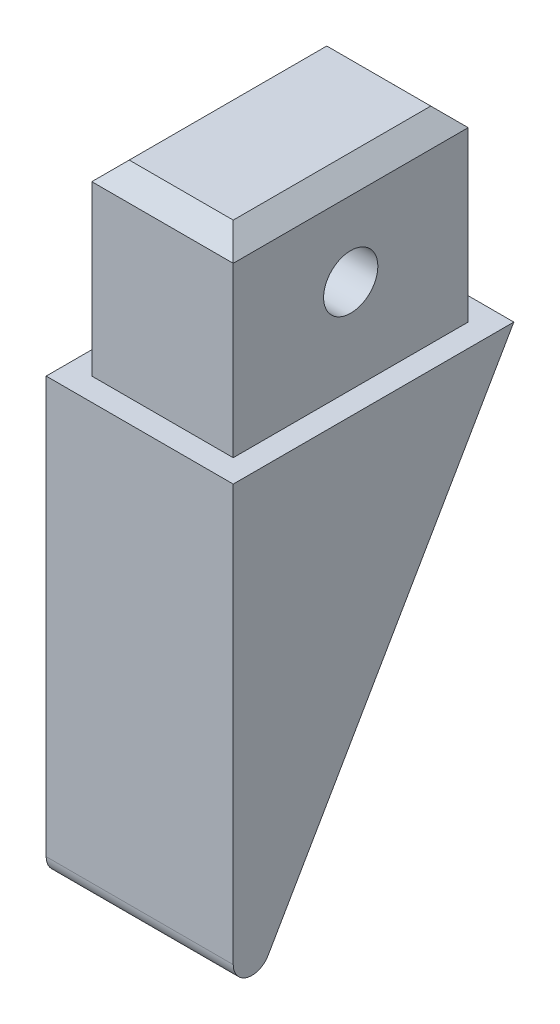
SolidWorks part; units mm, degrees
ref_plane "正面" through (0, 0, 0) normal (0, 0, 1) x (1, 0, 0)
ref_plane "平面" through (0, 0, 0) normal (0, 1, 0) x (1, 0, 0)
ref_plane "右側面" through (0, 0, 0) normal (1, 0, 0) x (0, 0, -1)
sketch "ｽｹｯﾁ1" plane through (0, 0, 0) normal (0, 1, 0) x (1, 0, 0)
  line L0 (-3.78, 6.28) -> (3.78, 6.28)
  line L1 (-5, -7.5) -> (5, -7.5) construction
  line L2 (-5, -7.5) -> (-5, 7.5) construction
  line L3 (-5, 7.5) -> (5, 7.5) construction
  line L4 (5, -7.5) -> (5, 7.5) construction
  line L5 (-5, -7.5) -> (5, 7.5) construction
  line L6 (-5, 7.5) -> (5, -7.5) construction
  line L7 (3.78, -6.28) -> (3.78, 6.28)
  line L8 (-3.78, -6.28) -> (3.78, -6.28)
  line L9 (-3.78, -6.28) -> (-3.78, 6.28)
  point P0 (0, 0)
  dimension "D1" = 15
  dimension "D2" = 10
  dimension "D3" = 1.22
extrude "ﾎﾞｽ - 押し出し1" add sketch "ｽｹｯﾁ1" along normal blind 10
chamfer "面取り1" distance 1 angle 45 4 edges at (0, 10, -6.28) (3.78, 10, 0) (0, 10, 6.28) (-3.78, 10, 0)
sketch "ｽｹｯﾁ3" plane through (0, 0, 0) normal (1, 0, 0) x (0, 0, -1)
  line L0 (-5.28, 10) -> (-6.28, 9) construction
  line L1 (6.28, 9) -> (5.28, 10) construction
  line L2 (5.28, 10) -> (-5.28, 10) construction
  line L3 (6.28, 0) -> (6.28, 9) construction
  line L4 (-6.28, 9) -> (-6.28, 0) construction
  line L5 (-6.28, 0) -> (6.28, 0) construction
  line L6 (-5.28, 10) -> (-6.28, 9)
  line L7 (6.28, 9) -> (5.28, 10)
  line L8 (5.28, 10) -> (-5.28, 10)
  line L9 (6.28, 0) -> (6.28, 9)
  line L10 (-6.28, 9) -> (-6.28, 0)
  line L11 (-6.28, 0) -> (6.28, 0)
  line L12 (0, 0) -> (7.5, 0)
  line L13 (7.5, 0) -> (-7.5, -25.9808)
  line L14 (-7.5, -25.9808) -> (-7.5, 0)
  line L15 (-7.5, 0) -> (-6.28, 0)
  dimension "D1" = 7.5
  dimension "D2" = 7.5
  dimension "D3" = 60
extrude "ﾎﾞｽ - 押し出し2" add sketch "ｽｹｯﾁ3" along normal mid plane 10 contours L15 L14 L13 L12 L11
sketch "ｽｹｯﾁ4" plane through (3.78, 0, 0) normal (1, 0, 0) x (0, 0, -1)
  line L4 (6.28, 0) -> (6.28, 9)
  line L5 (6.28, 9) -> (-6.28, 9)
  line L6 (-6.28, 9) -> (-6.28, 0)
  line L7 (-6.28, 0) -> (6.28, 0)
  line L8 (6.28, 0) -> (6.28, 9) construction
  line L9 (6.28, 9) -> (-6.28, 9) construction
  line L10 (-6.28, 9) -> (-6.28, 0) construction
  line L11 (-6.28, 0) -> (6.28, 0) construction
  circle A0 centre (0, 5) radius 1.45
  point P2 (0, 0)
  point P6 (0, 4.545)
  dimension "D3" = 2.9
  dimension "D2" = 5
  dimension "D1" = 0
extrude "ｶｯﾄ - 押し出し1" cut sketch "ｽｹｯﾁ4" against normal blind 10
fillet "ﾌｨﾚｯﾄ1" radius 1 1 edges at (0, -25.9808, 7.5)
